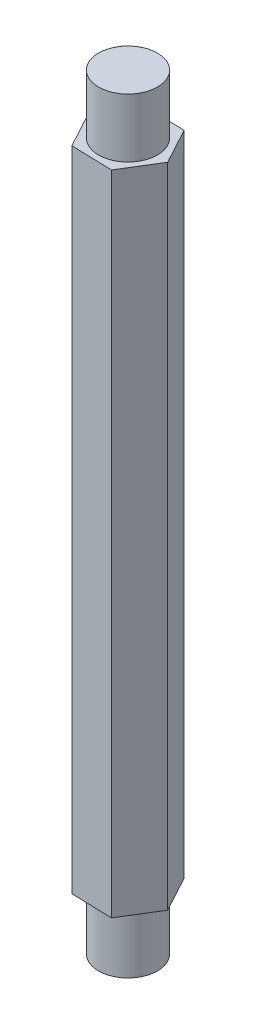
SolidWorks part; units mm, degrees
material "Brass"
ref_plane "Front Plane" through (0, 0, 0) normal (0, 0, 1) x (1, 0, 0)
ref_plane "Top Plane" through (0, 0, 0) normal (0, 1, 0) x (1, 0, 0)
ref_plane "Right Plane" through (0, 0, 0) normal (1, 0, 0) x (0, 0, -1)
sketch "Sketch1" plane through (0, 0, 0) normal (0, 1, 0) x (1, 0, 0)
  circle A0 centre (0, 0) radius 1.5
  dimension "D1" = 3
extrude "Boss-Extrude1" add sketch "Sketch1" along normal blind 3
sketch "Sketch2" plane through (0, 3, 0) normal (0, 1, 0) x (1, 0, 0)
  line L0 (0, 0) -> (-1.5, 0) construction
  line L1 (-0.9892, 1.828) -> (-2.0777, 0.0574)
  line L2 (-2.0777, 0.0574) -> (-1.0885, -1.7706)
  line L3 (-1.0885, -1.7706) -> (0.9892, -1.828)
  line L4 (0.9892, -1.828) -> (2.0777, -0.0574)
  line L5 (2.0777, -0.0574) -> (1.0885, 1.7706)
  line L6 (1.0885, 1.7706) -> (-0.9892, 1.828)
  circle A0 centre (0, 0) radius 1.8 construction
  circle A1 centre (0, 0) radius 1.5 construction
  dimension "D2" = 178.418
  dimension "D1" = 1.8
extrude "Boss-Extrude2" add sketch "Sketch2" along normal blind 33
sketch "Sketch3" plane through (0, 36, 0) normal (0, 1, 0) x (1, 0, 0)
  circle A0 centre (0, 0) radius 1.5
  dimension "D1" = 3
extrude "Boss-Extrude3" add sketch "Sketch3" along normal blind 3
